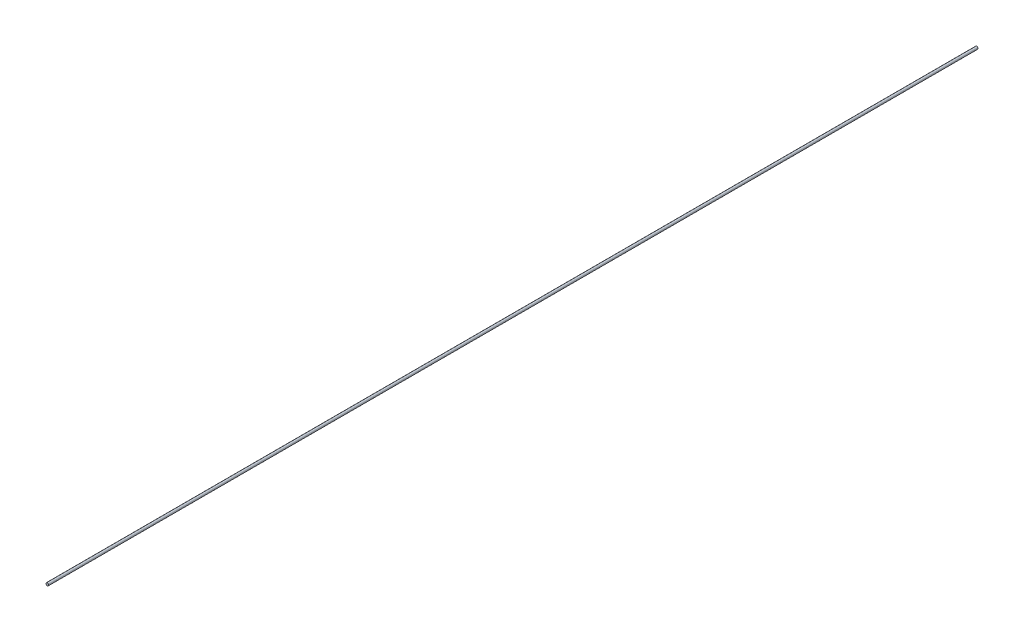
SolidWorks part; units mm, degrees
ref_plane "Front Plane" through (0, 0, 0) normal (0, 0, 1) x (1, 0, 0)
ref_plane "Top Plane" through (0, 0, 0) normal (0, 1, 0) x (1, 0, 0)
ref_plane "Right Plane" through (0, 0, 0) normal (1, 0, 0) x (0, 0, -1)
sketch "Sketch1" plane through (0, 0, 0) normal (0, 0, 1) x (1, 0, 0)
  circle A0 centre (0, 0) radius 1.5
  dimension "D1" = 3
extrude "Boss-Extrude1" add sketch "Sketch1" along normal blind 1060
